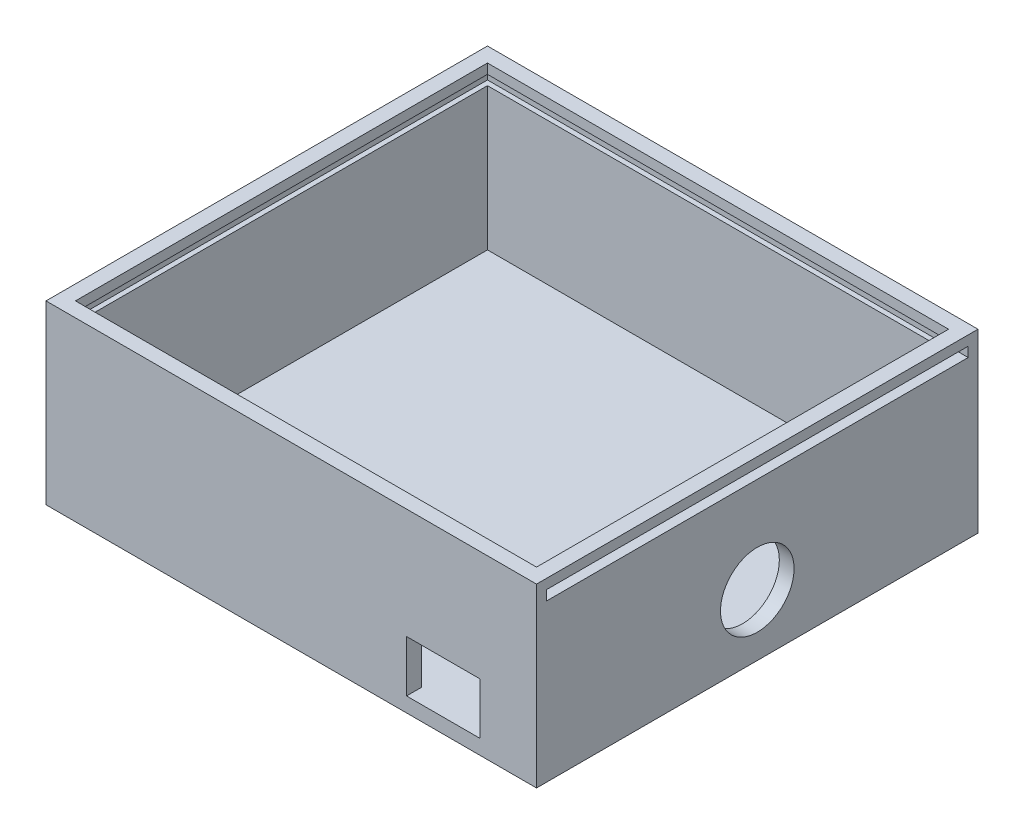
SolidWorks part; units mm, degrees
ref_plane "Front Plane" through (0, 0, 0) normal (0, 0, 1) x (1, 0, 0)
ref_plane "Top Plane" through (0, 0, 0) normal (0, 1, 0) x (1, 0, 0)
ref_plane "Right Plane" through (0, 0, 0) normal (1, 0, 0) x (0, 0, -1)
sketch "Sketch1" plane through (0, 0, 0) normal (0, 0, 1) x (1, 0, 0)
  line L1 (0, 0) -> (100, 0)
  line L2 (0, 0) -> (0, -36)
  line L3 (0, -36) -> (100, -36)
  line L4 (100, 0) -> (100, -36)
  dimension "D1" = 100
  dimension "D2" = 36
extrude "Boss-Extrude1" add sketch "Sketch1" along normal blind 90
shell "Shell2" thickness 3
sketch "Sketch3" plane through (0, 0, 90) normal (0, 0, 1) x (1, 0, 0)
  line L0 (100, -36) -> (100, 0) construction
  line L1 (88.5, -33) -> (73.5, -33)
  line L2 (88.5, -33) -> (88.5, -22.5)
  line L3 (88.5, -22.5) -> (73.5, -22.5)
  line L4 (73.5, -33) -> (73.5, -22.5)
  line L5 (0, -36) -> (100, -36) construction
  dimension "D1" = 15
  dimension "D2" = 11.5
  dimension "D3" = 3
  dimension "D4" = 10.5
extrude "Cut-Extrude3" cut sketch "Sketch3" against normal blind 10
sketch "Sketch5" plane through (100, 0, 0) normal (1, 0, 0) x (0, 0, -1)
  line L0 (0, -36) -> (0, 0) construction
  line L1 (-88, -2) -> (-2, -2)
  line L2 (-88, -2) -> (-88, -4)
  line L3 (-88, -4) -> (-2, -4)
  line L4 (-2, -2) -> (-2, -4)
  line L6 (-90, 0) -> (0, 0) construction
  dimension "D1" = 2
  dimension "D2" = 86
  dimension "D3" = 2
  dimension "D4" = 2
extrude "Cut-Extrude4" cut sketch "Sketch5" against normal blind 98
sketch "Sketch6" plane through (100, 0, 0) normal (1, 0, 0) x (0, 0, -1)
  line L0 (-45, 0) -> (-45, -36) construction
  line L1 (-90, 0) -> (0, 0) construction
  line L2 (-90, -36) -> (0, -36) construction
  line L3 (-45, -36) -> (-45, -31) construction
  circle A0 centre (-45, -23.5) radius 7.5
  dimension "D2" = 15
  dimension "D1" = 5
extrude "Cut-Extrude5" cut sketch "Sketch6" against normal blind 10 contours A0
